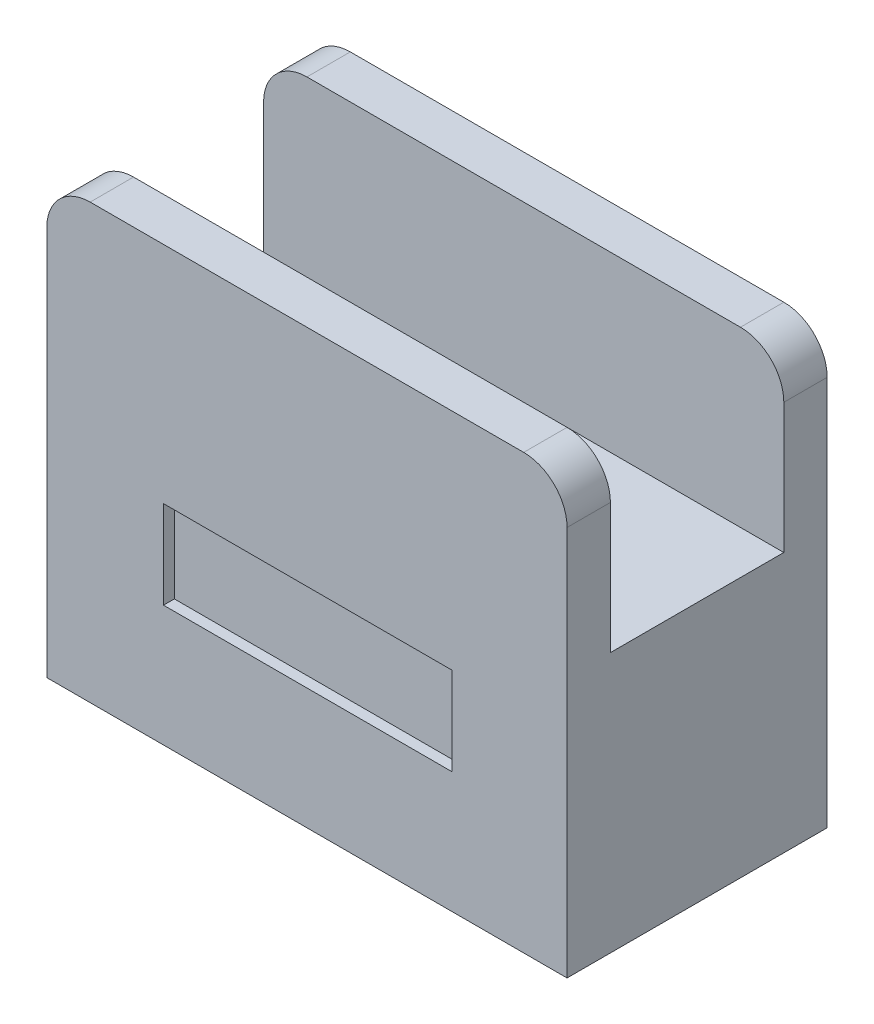
SolidWorks part; units mm, degrees
ref_plane "Front Plane" through (0, 0, 0) normal (0, 0, 1) x (1, 0, 0)
ref_plane "Top Plane" through (0, 0, 0) normal (0, 1, 0) x (1, 0, 0)
ref_plane "Right Plane" through (0, 0, 0) normal (1, 0, 0) x (0, 0, -1)
sketch "Sketch1" plane through (0, 0, 0) normal (0, 0, 1) x (1, 0, 0)
  line L1 (0, 0) -> (152.4, 0)
  line L2 (0, 0) -> (0, 76.2)
  line L3 (0, 76.2) -> (152.4, 76.2)
  line L4 (152.4, 0) -> (152.4, 76.2)
  dimension "D1" = 152.4
  dimension "D2" = 76.2
extrude "Boss-Extrude1" add sketch "Sketch1" along normal blind 76.2
sketch "Sketch2" plane through (0, 76.2, 0) normal (0, 1, 0) x (1, 0, 0)
  line L0 (152.4, -76.2) -> (152.4, 0) construction
  line L1 (0, 0) -> (152.4, 0)
  line L2 (0, 0) -> (0, -12.7)
  line L3 (0, -12.7) -> (152.4, -12.7)
  line L4 (152.4, 0) -> (152.4, -12.7)
  dimension "D1" = 12.7
extrude "Boss-Extrude2" add sketch "Sketch2" along normal blind 50.8
ref_plane "Plane1" through (0, 0, 38.1) normal (0, 0, 1) x (1, 0, 0)
mirror "Mirror1" about plane through (0, 0, 38.1) normal (0, 0, 1) of "Boss-Extrude2"
fillet "Fillet1" radius 12.7 4 edges at (0, 127, 6.35) (152.4, 127, 6.35) (0, 127, 69.85) (152.4, 127, 69.85)
sketch "Sketch3" plane through (0, 0, 76.2) normal (0, 0, 1) x (1, 0, 0)
  line L1 (34.1859, 61.2468) -> (118.6479, 61.2468)
  line L2 (34.1859, 61.2468) -> (34.1859, 35.4773)
  line L3 (34.1859, 35.4773) -> (118.6479, 35.4773)
  line L4 (118.6479, 61.2468) -> (118.6479, 35.4773)
extrude "Cut-Extrude1" cut sketch "Sketch3" against normal blind 3.175
